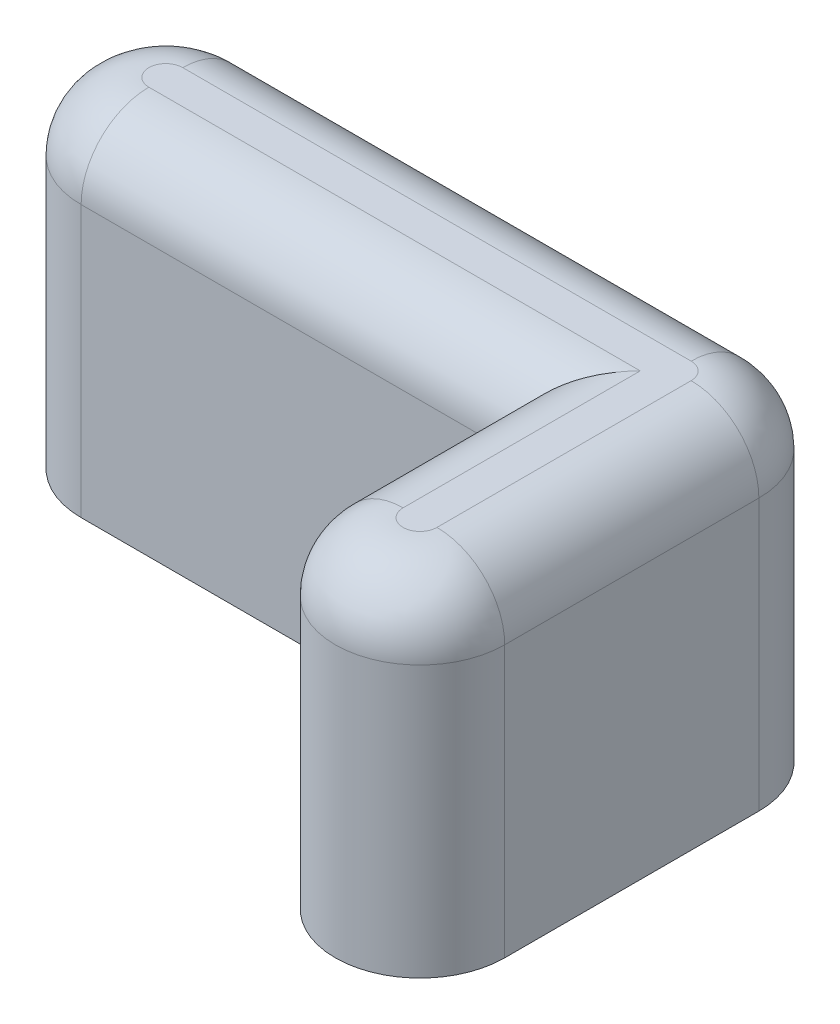
SolidWorks part; units mm, degrees
material "1060 Alloy"
ref_plane "Front Plane" through (0, 0, 0) normal (0, 0, 1) x (1, 0, 0)
ref_plane "Top Plane" through (0, 0, 0) normal (0, 1, 0) x (1, 0, 0)
ref_plane "Right Plane" through (0, 0, 0) normal (1, 0, 0) x (0, 0, -1)
sketch "Sketch1" plane through (0, 0, 0) normal (0, 1, 0) x (1, 0, 0)
  line L0 (-15, -5) -> (10, -5)
  line L1 (15, -5) -> (-15, -5) construction
  line L2 (15, -5) -> (15, 5) construction
  line L3 (15, 5) -> (-15, 5)
  line L4 (-15, -5) -> (-15, 5) construction
  line L5 (15, -5) -> (-15, 5) construction
  line L6 (15, 5) -> (-15, -5) construction
  line L7 (10, -15) -> (20, -15) construction
  line L8 (10, -15) -> (10, -5)
  line L10 (20, -15) -> (20, 0)
  arc A0 (-15, -5) -> (-15, 5) centre (-15, 0) cw
  arc A1 (15, 5) -> (20, 0) centre (15, 0) cw
  arc A2 (10, -15) -> (20, -15) centre (15, -15) ccw
  point P0 (0, 0)
  point P7 (15, -7.5)
  dimension "D1" = 30
  dimension "D2" = 10
  dimension "D3" = 15
extrude "Boss-Extrude1" add sketch "Sketch1" along normal blind 20 contours A0 L3 A1 L10 A2 L8 L0
fillet "Fillet1" radius 4 7 edges at (0, 20, -5) (-20, 20, 0) (10, 20, 10) (15, 20, 20) (20, 20, 7.5) (18.5355, 20, -3.5355) (-2.5, 20, 5)
sketch "Sketch2" plane through (0, 0, 0) normal (0, -1, 0) x (1, 0, 0)
  circle A0 centre (-15, 0) radius 2.75
  dimension "D1" = 5.5
extrude "Cut-Extrude1" cut sketch "Sketch2" against normal blind 1.5
pattern_linear "LPattern1" count 2 spacing 30 along (1, 0, 0) of "Cut-Extrude1"
